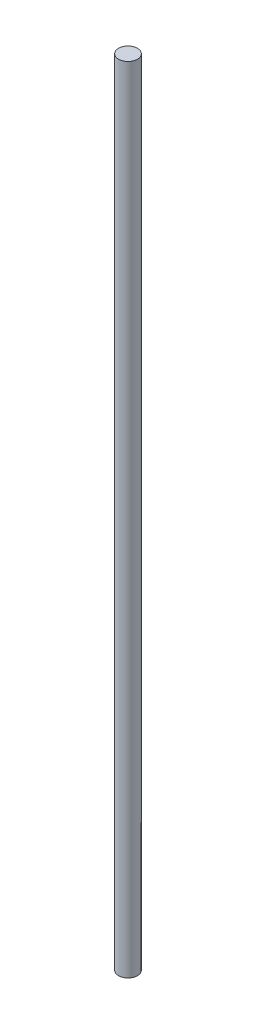
SolidWorks part; units mm, degrees
material "Custom Plastic"
ref_plane "Front Plane" through (0, 0, 0) normal (0, 0, 1) x (1, 0, 0)
ref_plane "Top Plane" through (0, 0, 0) normal (0, 1, 0) x (1, 0, 0)
ref_plane "Right Plane" through (0, 0, 0) normal (1, 0, 0) x (0, 0, -1)
sketch "Sketch1" plane through (0, 0, 0) normal (0, 1, 0) x (1, 0, 0)
  circle A0 centre (0, 0) radius 7.5
  dimension "D1" = 15
extrude "Boss-Extrude2" add sketch "Sketch1" along normal blind 630
